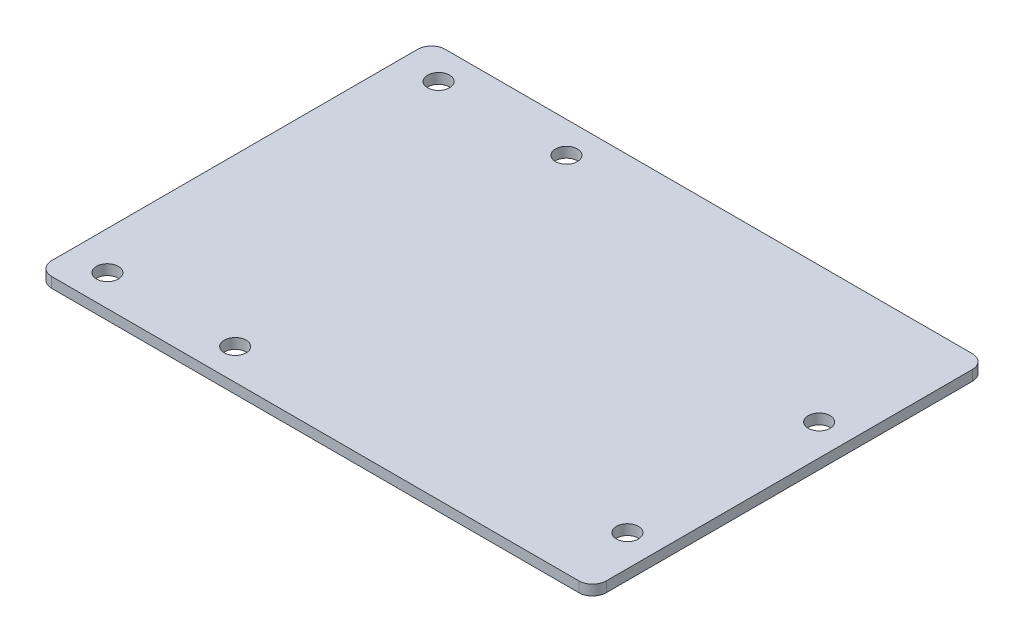
SolidWorks part; units mm, degrees
ref_plane "정면" through (0, 0, 0) normal (0, 0, 1) x (1, 0, 0)
ref_plane "윗면" through (0, 0, 0) normal (0, 1, 0) x (1, 0, 0)
ref_plane "우측면" through (0, 0, 0) normal (1, 0, 0) x (0, 0, -1)
sketch "스케치2" plane through (0, 0, 0) normal (0, 1, 0) x (1, 0, 0)
  line L0 (-43.3191, 28.67) -> (37.5, 28.67)
  line L1 (-43.3191, 28.67) -> (-43.3191, -28.67)
  line L2 (-43.3191, -28.67) -> (37.5, -28.67)
  line L3 (37.5, 28.67) -> (37.5, -28.67)
  line L4 (-43.3191, 28.67) -> (37.5, -28.67) construction
  line L5 (-43.3191, -28.67) -> (37.5, 28.67) construction
  line L7 (-5.5286, 0) -> (-67.9027, 0) construction
  arc A2 (31.36, 8.89) -> (34.56, 8.89) centre (32.96, 8.89) ccw
  arc A3 (34.56, 8.89) -> (31.36, 8.89) centre (32.96, 8.89) ccw
  arc A4 (31.36, -19.05) -> (34.56, -19.05) centre (32.96, -19.05) ccw
  arc A5 (34.56, -19.05) -> (31.36, -19.05) centre (32.96, -19.05) ccw
  arc A6 (-20.71, -24.13) -> (-17.51, -24.13) centre (-19.11, -24.13) ccw
  arc A7 (-17.51, -24.13) -> (-20.71, -24.13) centre (-19.11, -24.13) ccw
  circle A8 centre (-37.7363, 24.13) radius 1.6
  circle A9 centre (-37.7363, -24.13) radius 1.6
  arc A10 (-20.71, 24.13) -> (-17.51, 24.13) centre (-19.11, 24.13) cw
  arc A11 (-17.51, 24.13) -> (-20.71, 24.13) centre (-19.11, 24.13) cw
  point P0 (-2.9096, 0)
  point P20 (0, 0)
extrude "보스-돌출1" add sketch "스케치2" along normal blind 1.5
fillet "필렛1" radius 2 4 edges at (-43.3191, 0.75, -28.67) (37.5, 0.75, -28.67) (37.5, 0.75, 28.67) (-43.3191, 0.75, 28.67)
